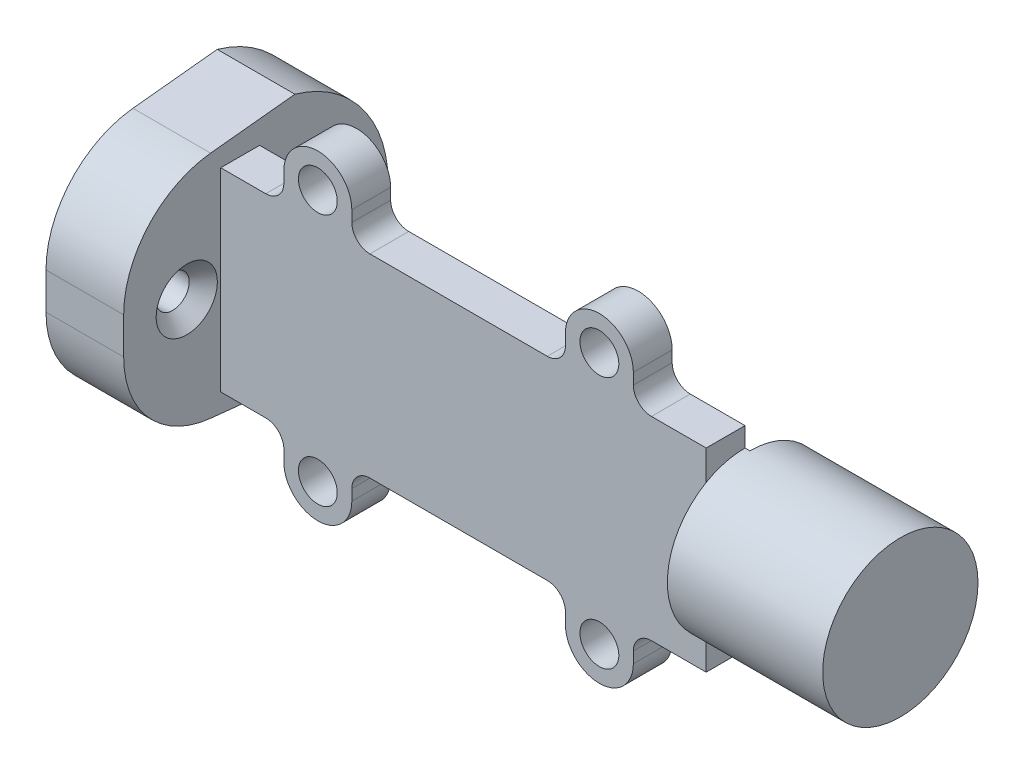
SolidWorks part; units mm, degrees
ref_plane "Plan de face" through (0, 0, 0) normal (0, 0, 1) x (1, 0, 0)
ref_plane "Plan de dessus" through (0, 0, 0) normal (0, 1, 0) x (1, 0, 0)
ref_plane "Plan de droite" through (0, 0, 0) normal (1, 0, 0) x (0, 0, -1)
sketch "Esquisse1" plane through (0, 0, 0) normal (0, 0, 1) x (1, 0, 0)
  line L16 (25, -10) -> (25, 10)
  line L17 (25, 10) -> (19.3642, 10)
  line L18 (17.5, 11.8642) -> (17.5, 13)
  line L19 (10.5, 13) -> (10.5, 11.8642)
  line L20 (8.6358, 10) -> (-9.6358, 10)
  line L21 (-11.5, 11.8642) -> (-11.5, 13)
  line L22 (-18.5, 13) -> (-18.5, 11.8642)
  line L23 (-20.3642, 10) -> (-25, 10)
  line L24 (-25, 10) -> (-25, -10)
  line L25 (-25, -10) -> (-20.3642, -10)
  line L26 (-18.5, -11.8642) -> (-18.5, -13)
  line L27 (-11.5, -13) -> (-11.5, -11.8642)
  line L28 (-9.6358, -10) -> (8.6358, -10)
  line L29 (10.5, -11.8642) -> (10.5, -13)
  line L30 (17.5, -13) -> (17.5, -11.8642)
  line L31 (19.3642, -10) -> (25, -10)
  line L32 (25, -10) -> (25, 10)
  line L33 (25, 10) -> (19.3642, 10)
  line L34 (17.5, 11.8642) -> (17.5, 13)
  line L35 (10.5, 13) -> (10.5, 11.8642)
  line L36 (8.6358, 10) -> (-9.6358, 10)
  line L37 (-11.5, 11.8642) -> (-11.5, 13)
  line L38 (-18.5, 13) -> (-18.5, 11.8642)
  line L39 (-20.3642, 10) -> (-25, 10)
  line L40 (-25, 10) -> (-25, -10)
  line L41 (-25, -10) -> (-20.3642, -10)
  line L42 (-18.5, -11.8642) -> (-18.5, -13)
  line L43 (-11.5, -13) -> (-11.5, -11.8642)
  line L44 (-9.6358, -10) -> (8.6358, -10)
  line L45 (10.5, -11.8642) -> (10.5, -13)
  line L46 (17.5, -13) -> (17.5, -11.8642)
  line L47 (19.3642, -10) -> (25, -10)
  arc A12 (17.5, 11.8642) -> (19.3642, 10) centre (19.3642, 11.8642) ccw
  arc A13 (17.5, 13) -> (10.5, 13) centre (14, 13) ccw
  arc A14 (8.6358, 10) -> (10.5, 11.8642) centre (8.6358, 11.8642) ccw
  arc A15 (-11.5, 11.8642) -> (-9.6358, 10) centre (-9.6358, 11.8642) ccw
  arc A16 (-11.5, 13) -> (-18.5, 13) centre (-15, 13) ccw
  arc A17 (-20.3642, 10) -> (-18.5, 11.8642) centre (-20.3642, 11.8642) ccw
  arc A18 (-18.5, -11.8642) -> (-20.3642, -10) centre (-20.3642, -11.8642) ccw
  arc A19 (-18.5, -13) -> (-11.5, -13) centre (-15, -13) ccw
  arc A20 (-9.6358, -10) -> (-11.5, -11.8642) centre (-9.6358, -11.8642) ccw
  arc A21 (10.5, -11.8642) -> (8.6358, -10) centre (8.6358, -11.8642) ccw
  arc A22 (10.5, -13) -> (17.5, -13) centre (14, -13) ccw
  arc A23 (19.3642, -10) -> (17.5, -11.8642) centre (19.3642, -11.8642) ccw
  arc A24 (17.5, 11.8642) -> (19.3642, 10) centre (19.3642, 11.8642) ccw
  arc A25 (17.5, 13) -> (10.5, 13) centre (14, 13) ccw
  arc A26 (8.6358, 10) -> (10.5, 11.8642) centre (8.6358, 11.8642) ccw
  arc A27 (-11.5, 11.8642) -> (-9.6358, 10) centre (-9.6358, 11.8642) ccw
  arc A28 (-11.5, 13) -> (-18.5, 13) centre (-15, 13) ccw
  arc A29 (-20.3642, 10) -> (-18.5, 11.8642) centre (-20.3642, 11.8642) ccw
  arc A30 (-18.5, -11.8642) -> (-20.3642, -10) centre (-20.3642, -11.8642) ccw
  arc A31 (-18.5, -13) -> (-11.5, -13) centre (-15, -13) ccw
  arc A32 (-9.6358, -10) -> (-11.5, -11.8642) centre (-9.6358, -11.8642) ccw
  arc A33 (10.5, -11.8642) -> (8.6358, -10) centre (8.6358, -11.8642) ccw
  arc A34 (10.5, -13) -> (17.5, -13) centre (14, -13) ccw
  arc A35 (19.3642, -10) -> (17.5, -11.8642) centre (19.3642, -11.8642) ccw
  dimension "D1" = 0
extrude "Boss.-Extru.1" add sketch "Esquisse1" along normal blind 4 contours L32 L33 A24 L34 A25 L35 A26 L36 A27 L37 A28 L38 A29 L39 L40 L41 A30 L42 A31 L43 A32 L44 A33 L45 A34 L46 A35 L47
sketch "Esquisse2" plane through (-25, 0, 0) normal (-1, 0, 0) x (0, 0, 1)
  line L9 (-3.6387, 12.7406) -> (5.0453, 11.8278)
  line L10 (14, 1.8826) -> (14, -1.8826)
  line L11 (5.0453, -11.8278) -> (-3.6387, -12.7406)
  arc A0 (5.0453, -11.8278) -> (14, -1.8826) centre (4, -1.8826) ccw
  arc A1 (-3.6387, 12.7406) -> (-3.6387, -12.7406) centre (0, 0) ccw
  arc A2 (14, 1.8826) -> (5.0453, 11.8278) centre (4, 1.8826) ccw
  point P4 (-13.25, 0)
  point P16 (14.25, 0)
  dimension "D2" = 10
  dimension "D4" = 14
  dimension "D5" = 84
  dimension "D6" = 84
  dimension "D1" = 13.25
extrude "Boss.-Extru.2" add sketch "Esquisse2" along normal up to surface (8 mm away)
sketch "Esquisse3" plane through (-33, 0, 0) normal (-1, 0, 0) x (0, 0, 1)
  circle A2 centre (0, 0) radius 10.25
  circle A3 centre (0, 0) radius 10.25
  dimension "D1" = 0.25
extrude "Enlèv. mat.-Extru.1" cut sketch "Esquisse3" against normal up to surface (2 mm away)
sketch "Esquisse6" plane through (0, 0, 0) normal (0, 0, -1) x (-1, 0, 0)
  circle A0 centre (15, -13) radius 2 construction
  circle A1 centre (-14, -13) radius 2 construction
  circle A2 centre (-14, 13) radius 2 construction
  circle A3 centre (15, 13) radius 2 construction
  circle A4 centre (15, -13) radius 2
  circle A5 centre (-14, -13) radius 2
  circle A6 centre (-14, 13) radius 2
  circle A7 centre (15, 13) radius 2
extrude "Enlèv. mat.-Extru.2" cut sketch "Esquisse6" against normal through all
sketch "Esquisse7" plane through (25, 0, 0) normal (1, 0, 0) x (0, 0, -1)
  line L1 (0, 10) -> (0, -10) construction
  line L2 (0, -10) -> (0, 10) construction
  circle A0 centre (0, 0) radius 8
  dimension "D1" = 16
extrude "Boss.-Extru.5" add sketch "Esquisse7" along normal blind 16
sketch "Esquisse8" plane through (25, 0, 0) normal (-1, 0, 0) x (0, 0, 1)
  line L1 (4, 6.9282) -> (4, -6.9282)
  line L2 (4, 6.9282) -> (4, -6.9282)
  arc A1 (4, -6.9282) -> (4, 6.9282) centre (0, 0) ccw
  arc A2 (4, -6.9282) -> (4, 6.9282) centre (0, 0) ccw
  dimension "D1" = 0
sketch "Esquisse9" plane through (0, 10, 0) normal (0, 1, 0) x (1, 0, 0)
  line L1 (25, 0) -> (25.5, 0)
  line L2 (25, 0) -> (25, 9.6018)
  line L3 (25, 9.6018) -> (25.5, 9.6018)
  line L4 (25.5, 0) -> (25.5, 9.6018)
  dimension "D1" = 0.5
extrude "Enlèv. mat.-Extru.3" cut sketch "Esquisse9" against normal through all and the other way through all
hole_wizard "Fraisage pour vis à tête fraisée M31" positions "Esquisse11" profile "Esquisse12" countersink size "M3" standard "ISO"
sketch "Esquisse11" plane through (-25, 0, 0) normal (1, 0, 0) x (0, 0, -1)
  point P0 (-7.5, 0)
  point P3 (7.5, 0)
sketch "Esquisse12" plane through (-25, 0, 7.5) normal (0, 1, 0) x (0, 0, -1)
  line L0 (0, 0) -> (0, 8)
  line L1 (0, 8) -> (1.7, 8)
  line L2 (1.7, 8) -> (1.7, 1.45)
  line L3 (1.7, 1.45) -> (3.15, 0)
  line L5 (3.15, 0) -> (0, 0)
  line L6 (-1.7, 1.45) -> (-3.15, 0) construction
  line L11 (0, -6.35) -> (0, 107.95) construction
  dimension "Diamètre du perçage jusqu'au prochain" = 3.4
  dimension "Profondeur du perçage jusqu'au prochain" = 8
  dimension "Diamètre du fraisage entrant" = 6.3
  dimension "Angle du fraisage entrant" = 90
